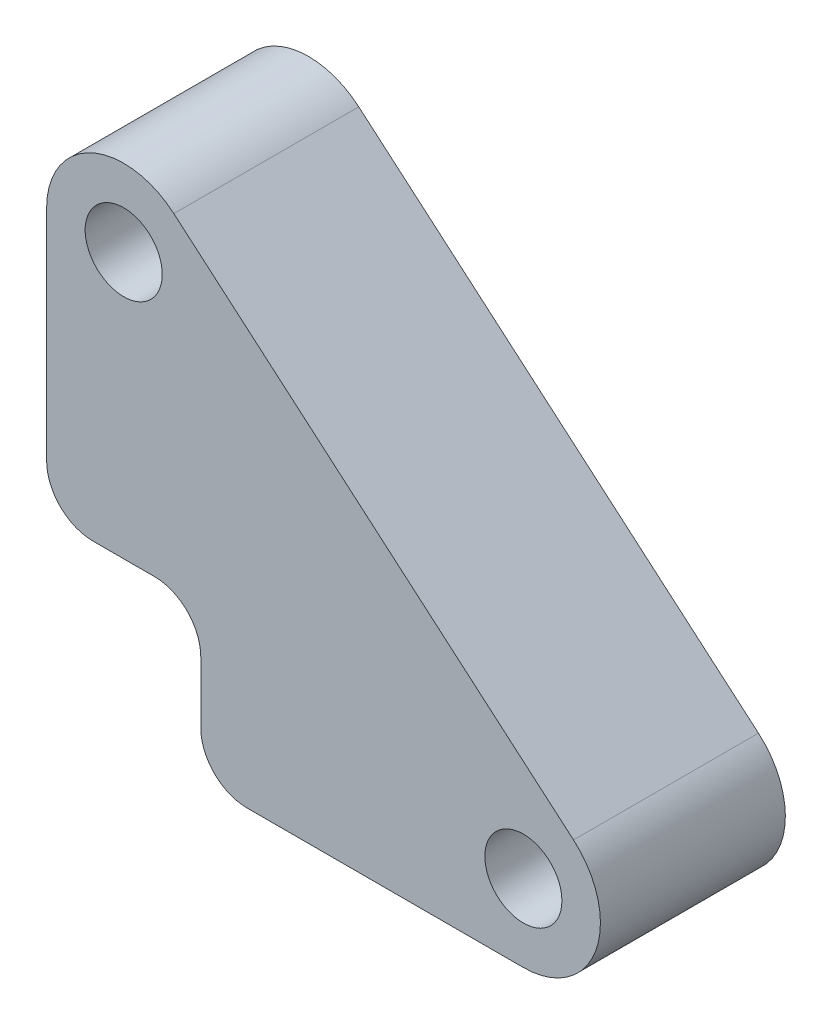
SolidWorks part; units mm, degrees
ref_plane "Front Plane" through (0, 0, 0) normal (0, 0, 1) x (1, 0, 0)
ref_plane "Top Plane" through (0, 0, 0) normal (0, 1, 0) x (1, 0, 0)
ref_plane "Right Plane" through (0, 0, 0) normal (1, 0, 0) x (0, 0, -1)
sketch "Sketch1" plane through (0, 0, 0) normal (0, 0, 1) x (1, 0, 0)
  line L0 (0, 10) -> (0, 54.4578)
  line L1 (16.5079, 62.0504) -> (68.3753, 17.5926)
  line L2 (61.8674, 0) -> (10, 0)
  arc A0 (0, 10) -> (10, 0) centre (10, 10) ccw
  arc A1 (68.3753, 17.5926) -> (61.8674, 0) centre (61.8674, 10) cw
  arc A2 (0, 54.4578) -> (16.5079, 62.0504) centre (10, 54.4578) cw
  point P6 (0, 0)
  point P9 (88.9, 0)
  point P12 (0, 76.2)
  dimension "D3" = 10
  dimension "D1" = 88.9
  dimension "D2" = 76.2
extrude "Boss-Extrude1" add sketch "Sketch1" along normal blind 24
sketch "Sketch2" plane through (0, 0, 24) normal (0, 0, 1) x (1, 0, 0)
  circle A0 centre (10, 54.4578) radius 5
  arc A1 (16.5079, 62.0504) -> (0, 54.4578) centre (10, 54.4578) ccw construction
  circle A2 centre (61.8674, 10) radius 5
  arc A3 (61.8674, 0) -> (68.3753, 17.5926) centre (61.8674, 10) ccw construction
  dimension "D1" = 10
extrude "Cut-Extrude1" cut sketch "Sketch2" against normal through all
sketch "Sketch3" plane through (0, 0, 0) normal (0, 0, -1) x (-1, 0, 0)
  line L1 (0, 0) -> (-20, 0)
  line L2 (0, 0) -> (0, 20)
  line L3 (0, 20) -> (-14, 20)
  line L4 (-20, 0) -> (-20, 14)
  arc A0 (-20, 14) -> (-14, 20) centre (-14, 14) cw
  point P7 (-20, 20)
  dimension "D3" = 6
  dimension "D1" = 20
  dimension "D2" = 20
extrude "Cut-Extrude2" cut sketch "Sketch3" against normal through all
fillet "Fillet1" radius 6 2 edges at (0, 20, 12) (20, 0, 12)
fillet "Fillet2" [suppressed] radius 3
